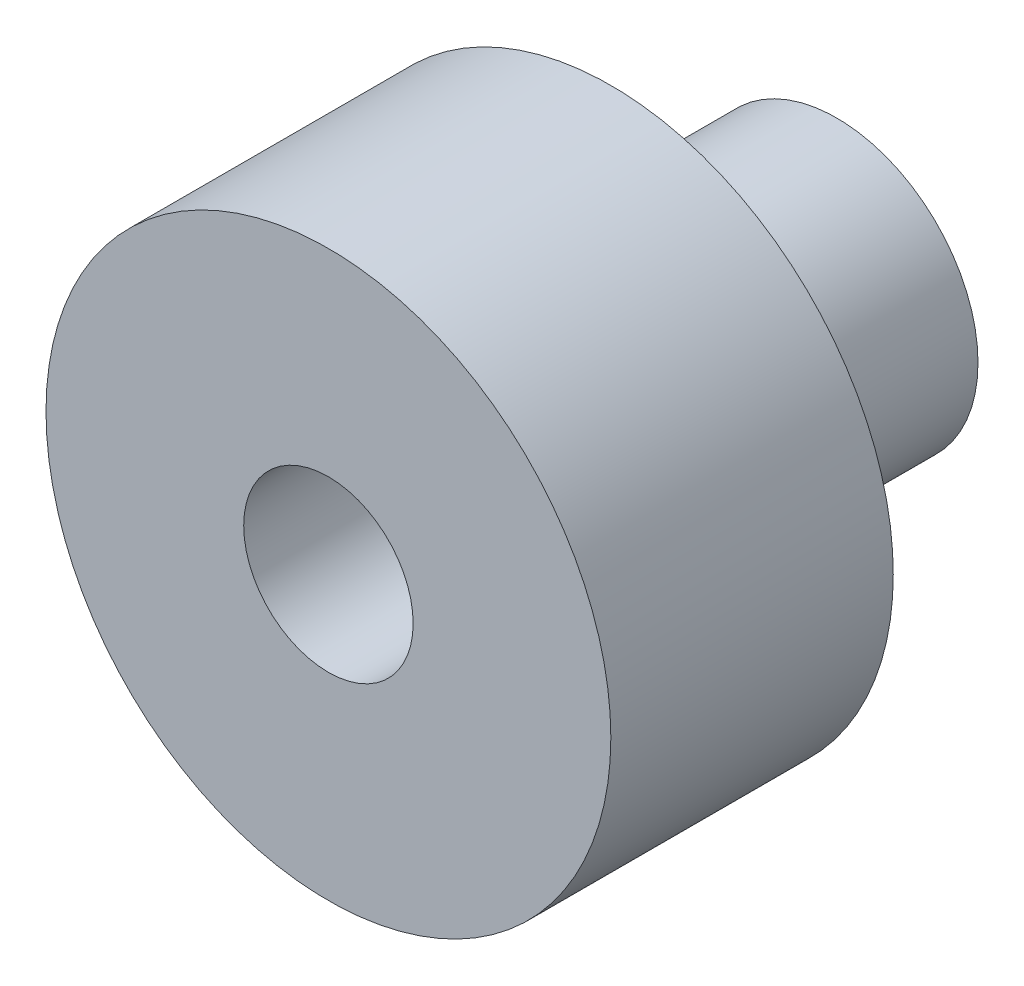
SolidWorks part; units mm, degrees
material "1060 Alloy"
ref_plane "Front" through (0, 0, 0) normal (0, 0, 1) x (1, 0, 0)
ref_plane "Top" through (0, 0, 0) normal (0, 1, 0) x (1, 0, 0)
ref_plane "Right" through (0, 0, 0) normal (1, 0, 0) x (0, 0, -1)
sketch "Sketch1" plane through (0, 0, 0) normal (0, 0, 1) x (1, 0, 0)
  circle A0 centre (0, 0) radius 10
  dimension "D1" = 20
extrude "Boss-Extrude1" add sketch "Sketch1" along normal blind 10
sketch "Sketch3" plane through (0, 0, 0) normal (0, 0, -1) x (-1, 0, 0)
  circle A0 centre (0, 0) radius 5
  dimension "D1" = 10
extrude "Boss-Extrude2" add sketch "Sketch3" along normal blind 8
sketch "Sketch4" plane through (0, 0, -8) normal (0, 0, -1) x (-1, 0, 0)
  circle A0 centre (0, 0) radius 3
  dimension "D1" = 6
extrude "Cut-Extrude1" cut sketch "Sketch4" against normal blind 27
sketch "Sketch5" plane through (0, 0, 0) normal (0, 1, 0) x (1, 0, 0)
  circle A0 centre (0, 5) radius 1.5
  dimension "D1" = 3
extrude "Cut-Extrude2" cut sketch "Sketch5" against normal blind 27
